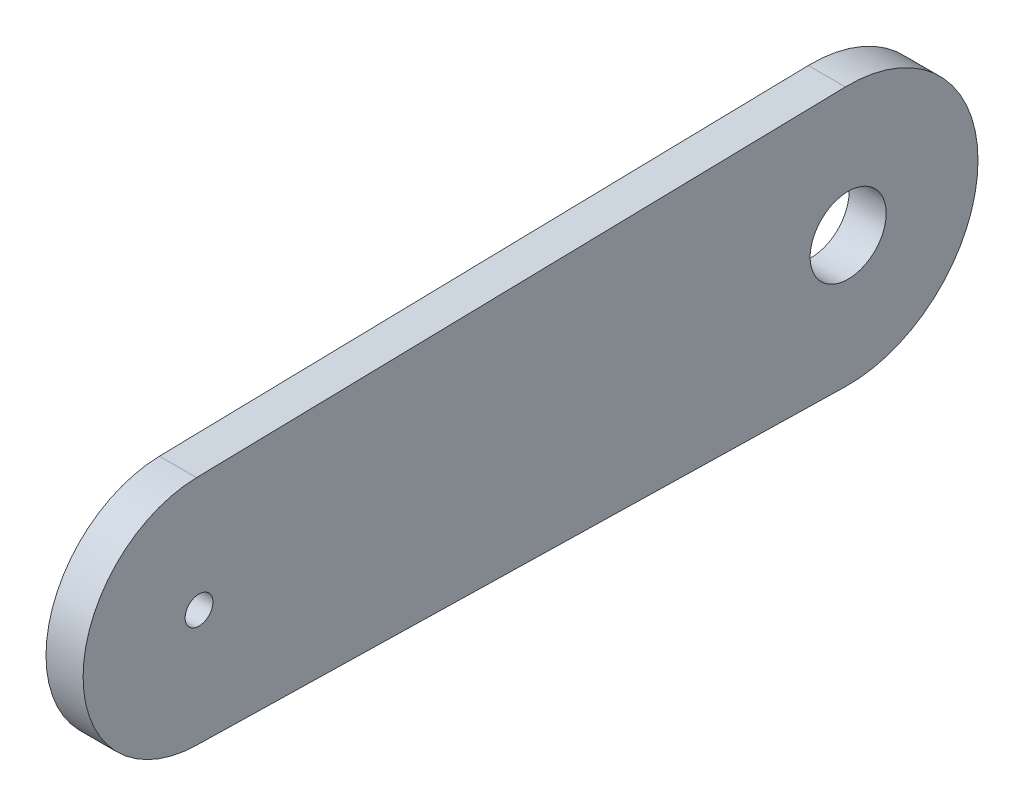
SolidWorks part; units mm, degrees
ref_plane "Alzado" through (0, 0, 0) normal (0, 0, 1) x (1, 0, 0)
ref_plane "Planta" through (0, 0, 0) normal (0, 1, 0) x (1, 0, 0)
ref_plane "Vista lateral" through (0, 0, 0) normal (1, 0, 0) x (0, 0, -1)
sketch "Croquis1" plane through (0, 0, 0) normal (1, 0, 0) x (0, 0, -1)
  line L0 (0, 0) -> (-98.2419, 0) construction
  line L1 (-70.2679, 12.4971) -> (-0.3, 13.9968)
  line L2 (-70.2679, -12.4971) -> (-0.3, -13.9968)
  circle A0 centre (0, 0) radius 4.1
  arc A1 (-0.3, -13.9968) -> (-0.3, 13.9968) centre (0, 0) ccw
  circle A2 centre (-70, 0) radius 1.5
  arc A3 (-70.2679, 12.4971) -> (-70.2679, -12.4971) centre (-70, 0) ccw
  dimension "D1" = 8.2
  dimension "D2" = 28
  dimension "D3" = 25
  dimension "D4" = 70
  dimension "D5" = 3
extrude "Saliente-Extruir1" add sketch "Croquis1" along normal blind 4
